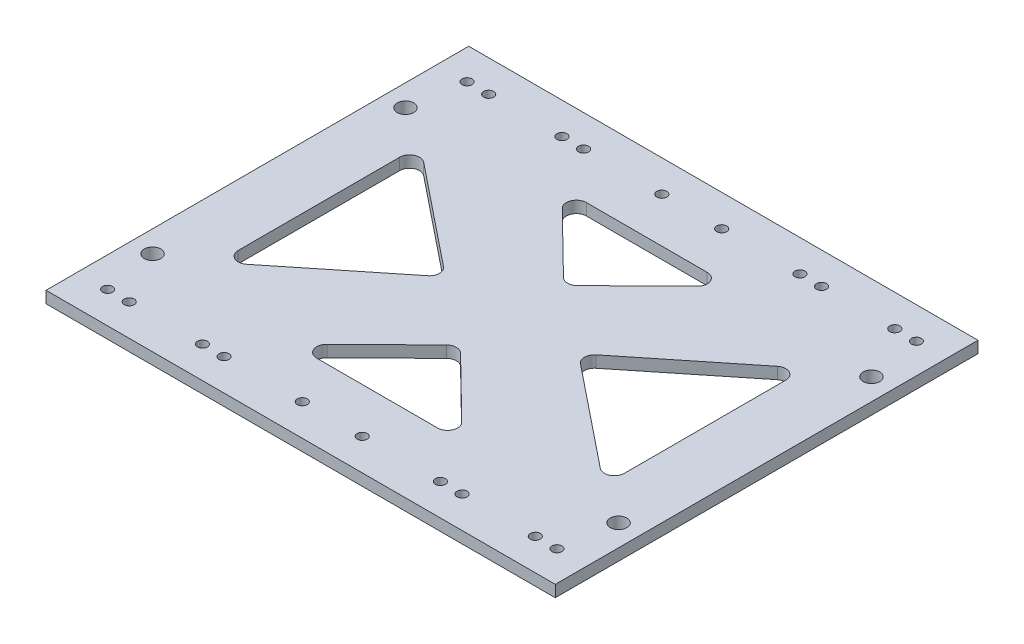
SolidWorks part; units mm, degrees
ref_plane "Front Plane" through (0, 0, 0) normal (0, 0, 1) x (1, 0, 0)
ref_plane "Top Plane" through (0, 0, 0) normal (0, 1, 0) x (1, 0, 0)
ref_plane "Right Plane" through (0, 0, 0) normal (1, 0, 0) x (0, 0, -1)
sketch "Sketch1" plane through (0, 0, 0) normal (0, 1, 0) x (1, 0, 0)
  line L0 (18.5, -63.5) -> (18.5, -33)
  line L1 (0, 0) -> (76.5, 0)
  line L2 (0, 0) -> (0, -63.5)
  line L3 (0, -63.5) -> (76.5, -63.5)
  line L4 (76.5, 0) -> (76.5, -63.5)
  line L5 (18.5, -33) -> (56.5, -63.5)
  line L6 (51, -23) -> (76.5, -23)
  line L7 (51, -23) -> (76.5, -48)
  circle A0 centre (9, -9.5) radius 1.5
  circle A1 centre (15.5, -9.5) radius 1.5
  circle A2 centre (37.5, -9.5) radius 1.5
  circle A3 centre (44, -9.5) radius 1.5
  circle A4 centre (67.5, -9.5) radius 1.5
  circle A5 centre (6.5, -25.5) radius 2.5
  dimension "D9" = 3
  dimension "D10" = 9
  dimension "D11" = 9.5
  dimension "D15" = 3
  dimension "D16" = 9
  dimension "D17" = 9.5
  dimension "D18" = 5
  dimension "D19" = 6.5
  dimension "D20" = 25.5
  dimension "D21" = 9.5
  dimension "D22" = 6.5
  dimension "D23" = 6.5
  dimension "D24" = 22
  dimension "D25" = 9.5
  dimension "D26" = 9.5
  dimension "D1" = 63.5
  dimension "D2" = 76.5
  dimension "D3" = 18.5
  dimension "D4" = 38
  dimension "D5" = 30.5
  dimension "D6" = 25
  dimension "D7" = 23
  dimension "D8" = 25.5
  dimension "D12" = 2
  dimension "D13" = 2
  dimension "D14" = 2
extrude "Boss-Extrude1" add sketch "Sketch1" along normal blind 3.5 contours L7 L6 L4 L1 L2 L3 L0 L5 A5 A4 A3 A2 A1 A0
mirror "Mirror1" about plane through (0, 3.5, 63.5) normal (0, 0, -1) of "Boss-Extrude1"
mirror "Mirror26" about plane through (76.5, 3.5, 0) normal (1, 0, 0) of "Boss-Extrude1"
mirror "Mirror27" about plane through (153, 3.5, 63.5) normal (0, 0, 1) of "Boss-Extrude1", "Mirror26"
fillet "Fillet1" radius 3 3 edges at (18.5, 1.75, 33) (18.5, 1.75, 94) (56.5, 1.75, 63.5)
fillet "Fillet4" radius 3 3 edges at (76.5, 1.75, 48) (102, 1.75, 23) (51, 1.75, 23)
fillet "Fillet5" radius 3 3 edges at (134.5, 1.75, 94) (96.5, 1.75, 63.5) (134.5, 1.75, 33)
fillet "Fillet6" radius 3 3 edges at (76.5, 1.75, 79) (51, 1.75, 104) (102, 1.75, 104)
